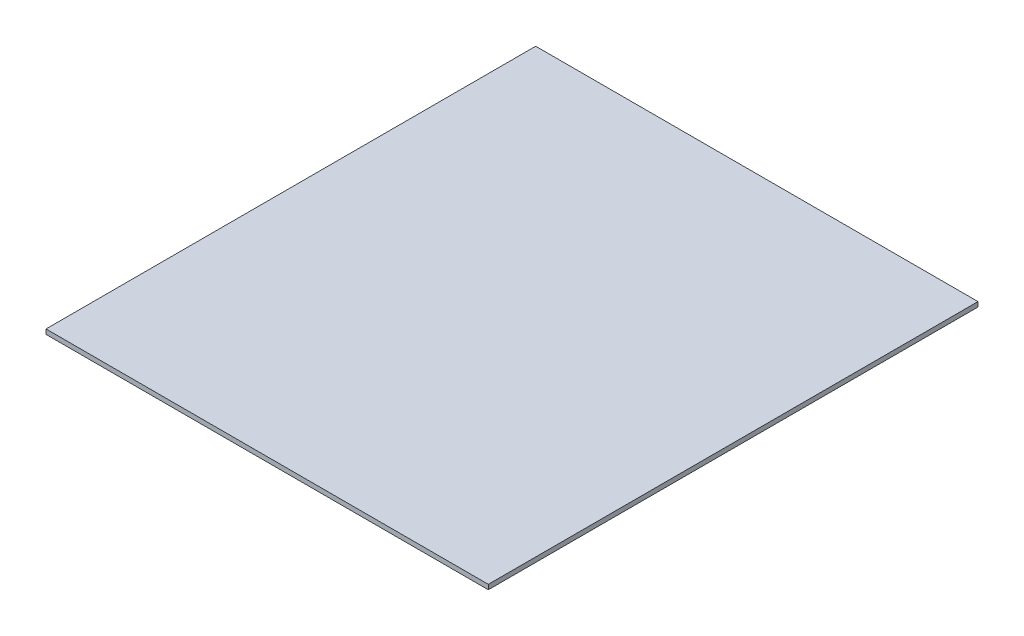
SolidWorks part; units mm, degrees
material "7050-T73510"
ref_plane "Front Plane" through (0, 0, 0) normal (0, 0, 1) x (1, 0, 0)
ref_plane "Top Plane" through (0, 0, 0) normal (0, 1, 0) x (1, 0, 0)
ref_plane "Right Plane" through (0, 0, 0) normal (1, 0, 0) x (0, 0, -1)
sketch "Sketch1" plane through (0, 0, 0) normal (0, 1, 0) x (1, 0, 0)
  line L1 (-140, 155) -> (140, 155)
  line L2 (-140, 155) -> (-140, -155)
  line L3 (-140, -155) -> (140, -155)
  line L4 (140, 155) -> (140, -155)
  line L5 (-140, 155) -> (140, -155) construction
  line L6 (-140, -155) -> (140, 155) construction
  point P0 (0, 0)
  dimension "D1" = 310
  dimension "D2" = 280
extrude "Boss-Extrude1" add sketch "Sketch1" along normal blind 3
